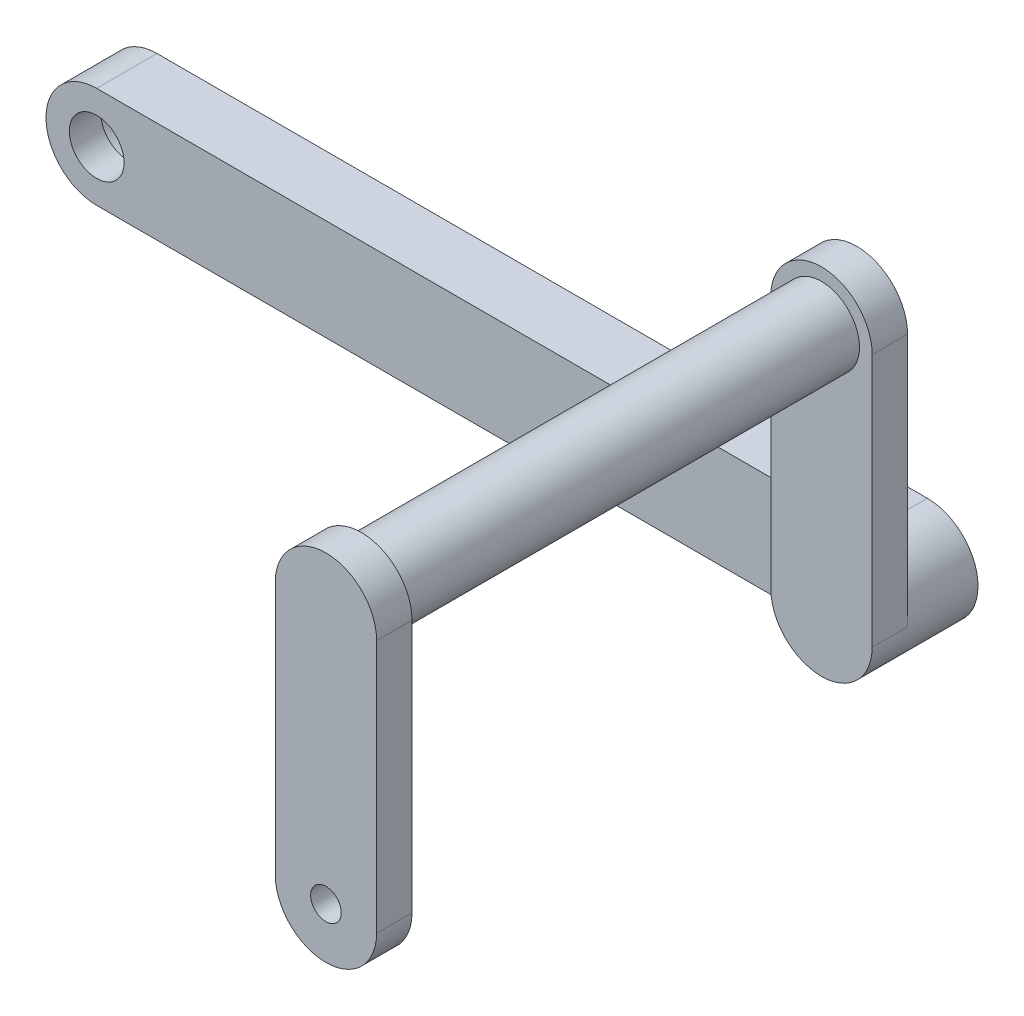
SolidWorks part; units mm, degrees
material "7075-T6 (SN)"
ref_plane "Alzado" through (0, 0, 0) normal (0, 0, 1) x (1, 0, 0)
ref_plane "Planta" through (0, 0, 0) normal (0, 1, 0) x (1, 0, 0)
ref_plane "Vista lateral" through (0, 0, 0) normal (1, 0, 0) x (0, 0, -1)
sketch "Croquis1" plane through (0, 0, 0) normal (0, 0, 1) x (1, 0, 0)
  line L0 (0, 0) -> (47.88, 0) construction
  line L1 (0, 3.15) -> (47.88, 3.15)
  line L2 (0, -3.15) -> (47.88, -3.15)
  circle A0 centre (0, 0) radius 1.7
  arc A1 (0, 3.15) -> (0, -3.15) centre (0, 0) ccw
  arc A2 (47.88, -3.15) -> (47.88, 3.15) centre (47.88, 0) ccw
  dimension "D1" = 3.4
  dimension "D3" = 6.3
  dimension "D4" = 6.3
  dimension "D2" = 47.88
extrude "Saliente-Extruir1" add sketch "Croquis1" along normal blind 3.75
sketch "Croquis2" plane through (0, 0, 3.75) normal (0, 0, 1) x (1, 0, 0)
  circle A0 centre (47.88, 0) radius 3.15
extrude "Saliente-Extruir2" add sketch "Croquis2" along normal blind 0.63
sketch "Croquis3" plane through (0, 0, 4.38) normal (0, 0, 1) x (1, 0, 0)
  line L0 (47.88, 0) -> (47.88, 15.75) construction
  line L1 (44.73, 15.75) -> (44.73, 0)
  line L2 (51.03, 15.75) -> (51.03, 0)
  arc A0 (44.73, 0) -> (51.03, 0) centre (47.88, 0) ccw
  arc A1 (51.03, 15.75) -> (44.73, 15.75) centre (47.88, 15.75) ccw
  dimension "D1" = 15.75
extrude "Saliente-Extruir3" add sketch "Croquis3" along normal blind 2.2
sketch "Croquis4" plane through (0, 0, 6.58) normal (0, 0, 1) x (1, 0, 0)
  circle A0 centre (47.88, 15.75) radius 2.365
  dimension "D1" = 4.73
extrude "Saliente-Extruir4" add sketch "Croquis4" along normal blind 28.6
sketch "Croquis5" plane through (0, 0, 35.18) normal (0, 0, 1) x (1, 0, 0)
  line L0 (44.73, 15.75) -> (44.73, 0)
  line L1 (51.03, 15.75) -> (51.03, 0)
  arc A0 (51.03, 15.75) -> (44.73, 15.75) centre (47.88, 15.75) ccw
  arc A1 (44.73, 0) -> (51.03, 0) centre (47.88, 0) ccw
  circle A2 centre (47.88, 0) radius 0.95
  dimension "D1" = 1.9
extrude "Saliente-Extruir5" add sketch "Croquis5" along normal blind 2.2
sketch "Croquis6" plane through (0, 0, 35.18) normal (0, 0, -1) x (-1, 0, 0)
  circle A0 centre (-47.88, 0) radius 1.25
  dimension "D1" = 2.5
extrude "Cortar-Extruir1" cut sketch "Croquis6" against normal blind 0.5
sketch "Croquis7" plane through (0, 0, 0) normal (0, 0, -1) x (-1, 0, 0)
  circle A0 centre (0, 0) radius 2.5
  dimension "D1" = 5
extrude "Cortar-Extruir2" cut sketch "Croquis7" against normal blind 1.8
